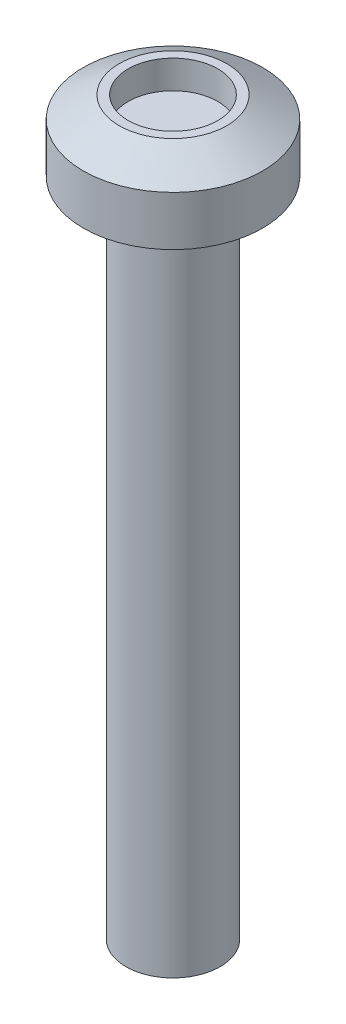
SolidWorks part; units mm, degrees
ref_plane "Front Plane" through (0, 0, 0) normal (0, 0, 1) x (1, 0, 0)
ref_plane "Top Plane" through (0, 0, 0) normal (0, 1, 0) x (1, 0, 0)
ref_plane "Right Plane" through (0, 0, 0) normal (1, 0, 0) x (0, 0, -1)
sketch "Sketch1" plane through (0, 0, 0) normal (0, 0, 1) x (1, 0, 0)
  line L0 (0, -14) -> (1, -14)
  line L1 (1, -14) -> (1, 0)
  line L2 (1, 0) -> (1.9, 0)
  line L3 (1.9, 0) -> (1.9, 1.05)
  line L4 (1.9, 1.05) -> (1.14, 1.5)
  line L5 (1.14, 1.5) -> (0, 1.5)
  line L6 (0, 1.5) -> (0, -14)
  line L7 (0, -10) -> (0, 1000) construction
revolve "Revolve1" add sketch "Sketch1" angle 360 about L7
cosmetic thread "Cosmetic Thread1"
ref_plane "Plane1" through (0, 1.5, 0) normal (0, 1, 0) x (1, 0, 0)
sketch "Sketch2" plane through (0, 1.5, 0) normal (0, 1, 0) x (1, 0, 0)
  circle A0 centre (0, 0) radius 0.95
extrude "Cut-Extrude1" cut sketch "Sketch2" against normal blind 0.6
